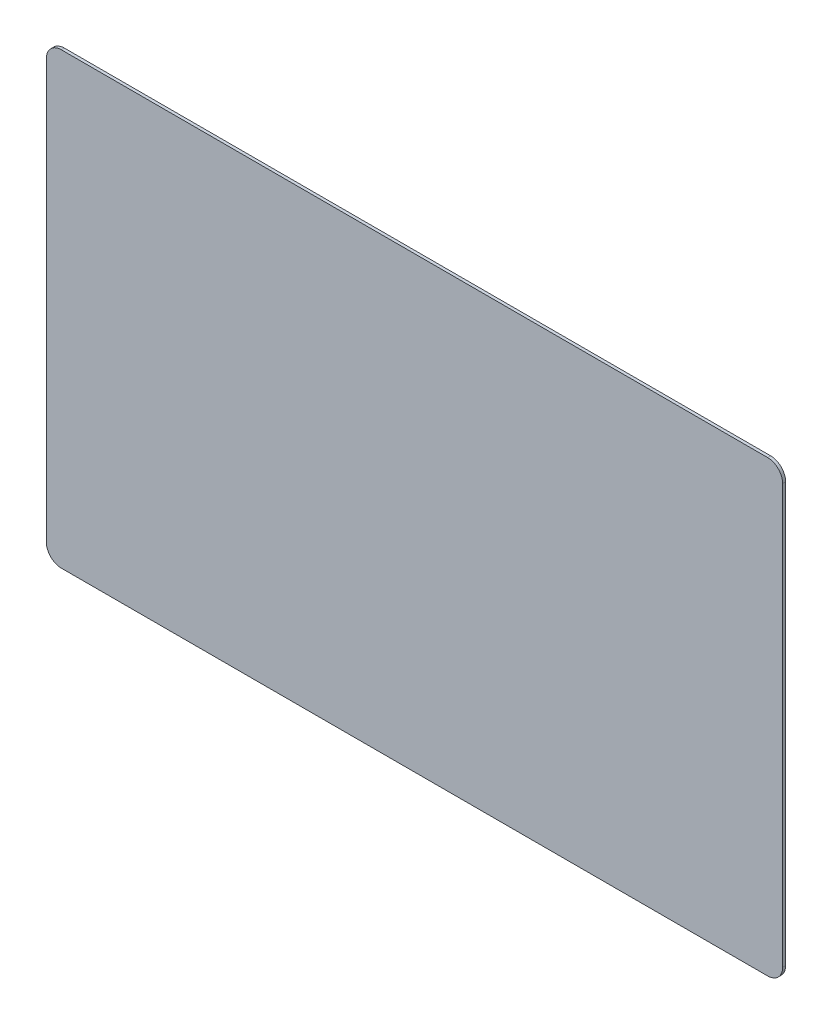
SolidWorks part; units mm, degrees
ref_plane "Front Plane" through (0, 0, 0) normal (0, 0, 1) x (1, 0, 0)
ref_plane "Top Plane" through (0, 0, 0) normal (0, 1, 0) x (1, 0, 0)
ref_plane "Right Plane" through (0, 0, 0) normal (1, 0, 0) x (0, 0, -1)
sketch "Sketch1" plane through (0, 0, 0) normal (0, 0, 1) x (1, 0, 0)
  line L0 (-246, -734) -> (-246, -434)
  line L5 (-246, -434) -> (246, -434)
  line L6 (246, -734) -> (246, -434)
  line L7 (-246, -734) -> (246, -734)
extrude "Boss-Extrude1" add sketch "Sketch1" along normal blind 2 contours L0 L5 L6 L7
fillet "Fillet1" radius 10 4 edges at (-246, -734, 1) (246, -734, 1) (246, -434, 1) (-246, -434, 1)
ref_plane "Plane1" through (0, -584, 0) normal (0, 1, 0) x (1, 0, 0)
extrude "Cut-Extrude1" cut sketch "Sketch2" against normal blind 600
sketch "Sketch2" plane through (-979.2099, 52.4771, 504) normal (0, 0, 1) x (0, 1, 0)
  line L1 (-781.4771, -1215.2099) -> (-501.4771, -1215.2099)
  line L2 (-781.4771, -1215.2099) -> (-781.4771, -743.2099)
  line L3 (-781.4771, -743.2099) -> (-501.4771, -743.2099)
  line L4 (-501.4771, -1215.2099) -> (-501.4771, -743.2099)
  line L5 (-781.4771, -1215.2099) -> (-501.4771, -743.2099) construction
  line L6 (-781.4771, -743.2099) -> (-501.4771, -1215.2099) construction
  line L10 (-206.4771, -743.2099) -> (-96.4771, -743.2099)
  line L11 (-216.4771, -753.2099) -> (-216.4771, -1205.2099)
  line L12 (-206.4771, -1215.2099) -> (-96.4771, -1215.2099)
  line L13 (-86.4771, -753.2099) -> (-86.4771, -1205.2099)
  arc A0 (-96.4771, -743.2099) -> (-86.4771, -753.2099) centre (-96.4771, -753.2099) cw
  arc A1 (-206.4771, -743.2099) -> (-216.4771, -753.2099) centre (-206.4771, -753.2099) ccw
  arc A2 (-96.4771, -1215.2099) -> (-86.4771, -1205.2099) centre (-96.4771, -1205.2099) ccw
  arc A3 (-216.4771, -1205.2099) -> (-206.4771, -1215.2099) centre (-206.4771, -1205.2099) ccw
  point P0 (-641.4771, -979.2099)
  point P21 (-86.4771, -743.2099)
  point P24 (-216.4771, -743.2099)
  point P27 (-86.4771, -1215.2099)
